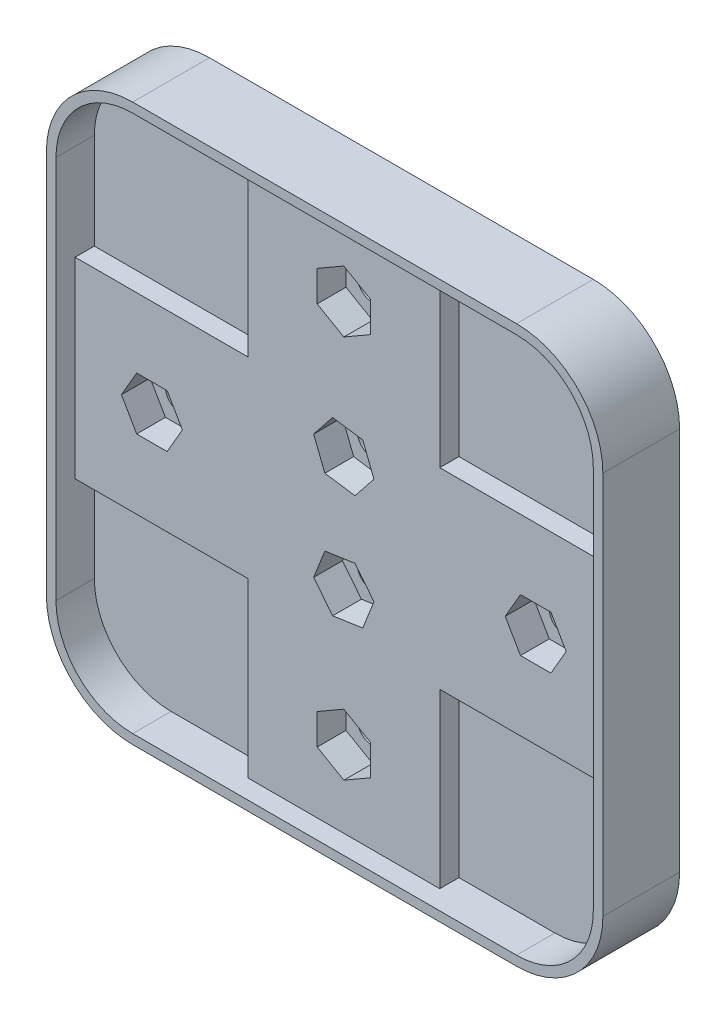
SolidWorks part; units mm, degrees
ref_plane "Front" through (0, 0, 0) normal (0, 0, 1) x (1, 0, 0)
ref_plane "Top" through (0, 0, 0) normal (0, 1, 0) x (1, 0, 0)
ref_plane "Right" through (0, 0, 0) normal (1, 0, 0) x (0, 0, -1)
sketch "草图1" plane through (0, 0, 0) normal (0, 0, 1) x (1, 0, 0)
  line L0 (-15.4063, 105.3183) -> (-15.4063, -125.7754) construction
  line L1 (-238.6458, 35.5371) -> (237.4375, 35.5371) construction
  line L2 (-35.4063, 64.5371) -> (4.5937, 64.5371)
  line L3 (13.5937, 55.5371) -> (13.5937, 15.5371)
  line L4 (4.5937, 6.5371) -> (-35.4063, 6.5371)
  line L5 (-44.4063, 15.5371) -> (-44.4063, 55.5371)
  arc A0 (13.5937, 55.5371) -> (4.5937, 64.5371) centre (4.5937, 55.5371) ccw
  arc A1 (4.5937, 6.5371) -> (13.5937, 15.5371) centre (4.5937, 15.5371) ccw
  arc A2 (-35.4063, 6.5371) -> (-44.4063, 15.5371) centre (-35.4063, 15.5371) cw
  arc A3 (-44.4063, 55.5371) -> (-35.4063, 64.5371) centre (-35.4063, 55.5371) cw
  point P16 (-44.4063, 64.5371)
  dimension "D5" = 9
  dimension "D6" = 9
  dimension "D1" = 29
  dimension "D2" = 58
  dimension "D3" = 58
  dimension "D4" = 29
extrude "凸台-拉伸1" add sketch "草图1" against normal blind 4
sketch "草图2" plane through (0, 0, 0) normal (0, 0, 1) x (1, 0, 0)
  line L0 (13.5937, 15.5371) -> (13.5937, 55.5371) construction
  line L1 (-35.4063, 6.5371) -> (4.5937, 6.5371) construction
  line L2 (-44.4063, 55.5371) -> (-44.4063, 15.5371) construction
  line L3 (4.5937, 64.5371) -> (-35.4063, 64.5371) construction
  line L4 (13.5937, 15.5371) -> (13.5937, 55.5371)
  line L5 (-35.4063, 6.5371) -> (4.5937, 6.5371)
  line L6 (-44.4063, 55.5371) -> (-44.4063, 15.5371)
  line L7 (4.5937, 64.5371) -> (-35.4063, 64.5371)
  line L8 (-35.4063, 63.5371) -> (-25.4063, 63.5371)
  line L9 (12.5937, 55.5371) -> (12.5937, 45.5371)
  line L10 (-43.4063, 55.5371) -> (-43.4063, 45.5371)
  line L11 (-35.4063, 7.5371) -> (-25.4063, 7.5371)
  line L12 (-25.4063, 63.5371) -> (-25.4063, 45.5371)
  line L13 (-15.4063, 63.5371) -> (-15.4063, 7.5371) construction
  line L14 (-44.4063, 35.5371) -> (13.5937, 35.5371) construction
  line L15 (-5.4063, 63.5371) -> (-5.4063, 45.5371)
  line L16 (-25.4063, 45.5371) -> (-43.4063, 45.5371)
  line L17 (-5.4063, 45.5371) -> (12.5937, 45.5371)
  line L18 (-5.4063, 25.5371) -> (12.5937, 25.5371)
  line L19 (-25.4063, 25.5371) -> (-43.4063, 25.5371)
  line L20 (-25.4063, 25.5371) -> (-25.4063, 7.5371)
  line L21 (-5.4063, 25.5371) -> (-5.4063, 7.5371)
  line L22 (-43.4063, 25.5371) -> (-43.4063, 15.5371)
  line L23 (-5.4063, 7.5371) -> (4.5937, 7.5371)
  line L24 (12.5937, 25.5371) -> (12.5937, 15.5371)
  line L25 (-5.4063, 63.5371) -> (4.5937, 63.5371)
  arc A0 (13.5937, 55.5371) -> (4.5937, 64.5371) centre (4.5937, 55.5371) ccw construction
  arc A1 (4.5937, 6.5371) -> (13.5937, 15.5371) centre (4.5937, 15.5371) ccw construction
  arc A2 (-44.4063, 15.5371) -> (-35.4063, 6.5371) centre (-35.4063, 15.5371) ccw construction
  arc A3 (-35.4063, 64.5371) -> (-44.4063, 55.5371) centre (-35.4063, 55.5371) ccw construction
  arc A4 (13.5937, 55.5371) -> (4.5937, 64.5371) centre (4.5937, 55.5371) ccw
  arc A5 (4.5937, 6.5371) -> (13.5937, 15.5371) centre (4.5937, 15.5371) ccw
  arc A6 (-44.4063, 15.5371) -> (-35.4063, 6.5371) centre (-35.4063, 15.5371) ccw
  arc A7 (-35.4063, 64.5371) -> (-44.4063, 55.5371) centre (-35.4063, 55.5371) ccw
  arc A8 (-35.4063, 7.5371) -> (-43.4063, 15.5371) centre (-35.4063, 15.5371) cw
  arc A9 (4.5937, 7.5371) -> (12.5937, 15.5371) centre (4.5937, 15.5371) ccw
  arc A10 (12.5937, 55.5371) -> (4.5937, 63.5371) centre (4.5937, 55.5371) ccw
  arc A11 (-43.4063, 55.5371) -> (-35.4063, 63.5371) centre (-35.4063, 55.5371) cw
  dimension "D5" = 8
  dimension "D1" = 1
  dimension "D2" = 1
  dimension "D3" = 1
  dimension "D4" = 1
  dimension "D6" = 10
  dimension "D7" = 10
  dimension "D8" = 10
extrude "凸台-拉伸2" add sketch "草图2" along normal blind 2
sketch "草图3" plane through (0, 0, 2) normal (0, 0, 1) x (1, 0, 0)
  line L0 (-43.4063, 55.5371) -> (-43.4063, 45.5371) construction
  line L1 (-43.4063, 25.5371) -> (-43.4063, 15.5371) construction
  line L2 (-35.4063, 7.5371) -> (-25.4063, 7.5371) construction
  line L3 (-5.4063, 7.5371) -> (4.5937, 7.5371) construction
  line L4 (12.5937, 15.5371) -> (12.5937, 25.5371) construction
  line L5 (12.5937, 45.5371) -> (12.5937, 55.5371) construction
  line L6 (4.5937, 63.5371) -> (-5.4063, 63.5371) construction
  line L7 (-25.4063, 63.5371) -> (-35.4063, 63.5371) construction
  line L8 (13.5937, 15.5371) -> (13.5937, 55.5371) construction
  line L9 (-35.4063, 6.5371) -> (4.5937, 6.5371) construction
  line L10 (-44.4063, 55.5371) -> (-44.4063, 15.5371) construction
  line L11 (4.5937, 64.5371) -> (-35.4063, 64.5371) construction
  line L12 (-43.4063, 55.5371) -> (-43.4063, 45.5371)
  line L13 (-43.4063, 25.5371) -> (-43.4063, 15.5371)
  line L14 (-35.4063, 7.5371) -> (-25.4063, 7.5371)
  line L15 (-5.4063, 7.5371) -> (4.5937, 7.5371)
  line L16 (12.5937, 15.5371) -> (12.5937, 25.5371)
  line L17 (12.5937, 45.5371) -> (12.5937, 55.5371)
  line L18 (4.5937, 63.5371) -> (-5.4063, 63.5371)
  line L19 (-25.4063, 63.5371) -> (-35.4063, 63.5371)
  line L20 (13.5937, 15.5371) -> (13.5937, 55.5371)
  line L21 (-35.4063, 6.5371) -> (4.5937, 6.5371)
  line L22 (-44.4063, 55.5371) -> (-44.4063, 15.5371)
  line L23 (4.5937, 64.5371) -> (-35.4063, 64.5371)
  line L24 (-25.4063, 63.5371) -> (-5.4063, 63.5371)
  line L25 (12.5937, 45.5371) -> (12.5937, 25.5371)
  line L26 (-5.4063, 7.5371) -> (-25.4063, 7.5371)
  line L27 (-43.4063, 45.5371) -> (-43.4063, 25.5371)
  arc A0 (-43.4063, 15.5371) -> (-35.4063, 7.5371) centre (-35.4063, 15.5371) ccw construction
  arc A1 (4.5937, 7.5371) -> (12.5937, 15.5371) centre (4.5937, 15.5371) ccw construction
  arc A2 (12.5937, 55.5371) -> (4.5937, 63.5371) centre (4.5937, 55.5371) ccw construction
  arc A3 (-35.4063, 63.5371) -> (-43.4063, 55.5371) centre (-35.4063, 55.5371) ccw construction
  arc A4 (13.5937, 55.5371) -> (4.5937, 64.5371) centre (4.5937, 55.5371) ccw construction
  arc A5 (4.5937, 6.5371) -> (13.5937, 15.5371) centre (4.5937, 15.5371) ccw construction
  arc A6 (-44.4063, 15.5371) -> (-35.4063, 6.5371) centre (-35.4063, 15.5371) ccw construction
  arc A7 (-35.4063, 64.5371) -> (-44.4063, 55.5371) centre (-35.4063, 55.5371) ccw construction
  arc A8 (-43.4063, 15.5371) -> (-35.4063, 7.5371) centre (-35.4063, 15.5371) ccw
  arc A9 (4.5937, 7.5371) -> (12.5937, 15.5371) centre (4.5937, 15.5371) ccw
  arc A10 (12.5937, 55.5371) -> (4.5937, 63.5371) centre (4.5937, 55.5371) ccw
  arc A11 (-35.4063, 63.5371) -> (-43.4063, 55.5371) centre (-35.4063, 55.5371) ccw
  arc A12 (13.5937, 55.5371) -> (4.5937, 64.5371) centre (4.5937, 55.5371) ccw
  arc A13 (4.5937, 6.5371) -> (13.5937, 15.5371) centre (4.5937, 15.5371) ccw
  arc A14 (-44.4063, 15.5371) -> (-35.4063, 6.5371) centre (-35.4063, 15.5371) ccw
  arc A15 (-35.4063, 64.5371) -> (-44.4063, 55.5371) centre (-35.4063, 55.5371) ccw
extrude "凸台-拉伸3" add sketch "草图3" along normal blind 2
sketch "草图4" plane through (0, 0, 2) normal (0, 0, 1) x (1, 0, 0)
  line L0 (-15.4063, 63.5371) -> (-15.4063, 7.5371) construction
  line L1 (-5.4063, 63.5371) -> (-25.4063, 63.5371) construction
  line L2 (-35.4063, 7.5371) -> (4.5937, 7.5371) construction
  line L3 (-43.4063, 35.5371) -> (12.5937, 35.5371) construction
  line L4 (-43.4063, 45.5371) -> (-43.4063, 25.5371) construction
  line L5 (12.5937, 25.5371) -> (12.5937, 45.5371) construction
  circle A0 centre (-15.4063, 41.5371) radius 1.6
  circle A1 centre (-15.4063, 29.5371) radius 1.6
  circle A2 centre (4.5937, 35.5371) radius 1.6
  circle A3 centre (-35.4063, 35.5371) radius 1.6
  dimension "D4" = 3.2
  dimension "D5" = 3.2
  dimension "D6" = 3.2
  dimension "D7" = 3.2
  dimension "D8" = 20
  dimension "D1" = 12
  dimension "D2" = 40
  dimension "D3" = 6
extrude "切除-拉伸1" cut sketch "草图4" against normal blind 10
sketch "草图5" plane through (0, 0, 2) normal (0, 0, 1) x (1, 0, 0)
  line L1 (-13.4319, 44.0241) -> (-16.5729, 44.4904)
  line L2 (-16.5729, 44.4904) -> (-18.5473, 42.0034)
  line L3 (-18.5473, 42.0034) -> (-17.3806, 39.0501)
  line L4 (-17.3806, 39.0501) -> (-14.2396, 38.5837)
  line L5 (-14.2396, 38.5837) -> (-12.2652, 41.0708)
  line L6 (-12.2652, 41.0708) -> (-13.4319, 44.0241)
  line L7 (1.4183, 35.5371) -> (3.006, 32.7871)
  line L8 (3.006, 32.7871) -> (6.1815, 32.7871)
  line L9 (6.1815, 32.7871) -> (7.7692, 35.5371)
  line L10 (7.7692, 35.5371) -> (6.1815, 38.2871)
  line L11 (6.1815, 38.2871) -> (3.006, 38.2871)
  line L12 (3.006, 38.2871) -> (1.4183, 35.5371)
  line L13 (-13.4319, 27.0501) -> (-12.2652, 30.0034)
  line L14 (-12.2652, 30.0034) -> (-14.2396, 32.4904)
  line L15 (-14.2396, 32.4904) -> (-17.3806, 32.0241)
  line L16 (-17.3806, 32.0241) -> (-18.5473, 29.0708)
  line L17 (-18.5473, 29.0708) -> (-16.5729, 26.5837)
  line L18 (-16.5729, 26.5837) -> (-13.4319, 27.0501)
  line L19 (-32.2308, 35.5371) -> (-33.8185, 38.2871)
  line L20 (-33.8185, 38.2871) -> (-36.994, 38.2871)
  line L21 (-36.994, 38.2871) -> (-38.5817, 35.5371)
  line L22 (-38.5817, 35.5371) -> (-36.994, 32.7871)
  line L23 (-36.994, 32.7871) -> (-33.8185, 32.7871)
  line L24 (-33.8185, 32.7871) -> (-32.2308, 35.5371)
  circle A0 centre (-15.4063, 41.5371) radius 2.75 construction
  circle A1 centre (4.5937, 35.5371) radius 2.75 construction
  circle A2 centre (-15.4063, 29.5371) radius 2.75 construction
  circle A3 centre (-35.4063, 35.5371) radius 2.75 construction
  dimension "D1" = 5.5
  dimension "D2" = 5.5
  dimension "D3" = 5.5
  dimension "D4" = 5.5
extrude "切除-拉伸2" cut sketch "草图5" against normal blind 3
sketch "草图7" plane through (0, 0, 2) normal (0, 0, 1) x (1, 0, 0)
  line L0 (-43.4063, 35.5371) -> (12.2885, 35.5371) construction
  line L1 (-43.4063, 45.5371) -> (-43.4063, 25.5371) construction
  line L2 (-5.4063, 25.5371) -> (-5.4063, 7.5371) construction
  circle A0 centre (-15.4063, 15.5371) radius 1.6
  circle A1 centre (-15.4063, 55.5371) radius 1.6
  dimension "D1" = 3.2
  dimension "D2" = 3.2
  dimension "D3" = 40
  dimension "D4" = 20
  dimension "D5" = 10
extrude "切除-拉伸3" cut sketch "草图7" against normal blind 10
sketch "草图8" plane through (0, 0, 2) normal (0, 0, 1) x (1, 0, 0)
  line L1 (-15.4063, 18.7414) -> (-18.1813, 17.1392)
  line L2 (-18.1813, 17.1392) -> (-18.1813, 13.9349)
  line L3 (-18.1813, 13.9349) -> (-15.4063, 12.3328)
  line L4 (-15.4063, 12.3328) -> (-12.6313, 13.9349)
  line L5 (-12.6313, 13.9349) -> (-12.6313, 17.1392)
  line L6 (-12.6313, 17.1392) -> (-15.4063, 18.7414)
  line L7 (-15.4063, 58.7414) -> (-18.1813, 57.1392)
  line L8 (-18.1813, 57.1392) -> (-18.1813, 53.9349)
  line L9 (-18.1813, 53.9349) -> (-15.4063, 52.3328)
  line L10 (-15.4063, 52.3328) -> (-12.6313, 53.9349)
  line L11 (-12.6313, 53.9349) -> (-12.6313, 57.1392)
  line L12 (-12.6313, 57.1392) -> (-15.4063, 58.7414)
  circle A0 centre (-15.4063, 15.5371) radius 2.775 construction
  circle A1 centre (-15.4063, 55.5371) radius 2.775 construction
  dimension "D1" = 5.55
  dimension "D2" = 5.55
extrude "切除-拉伸4" cut sketch "草图8" against normal blind 3
